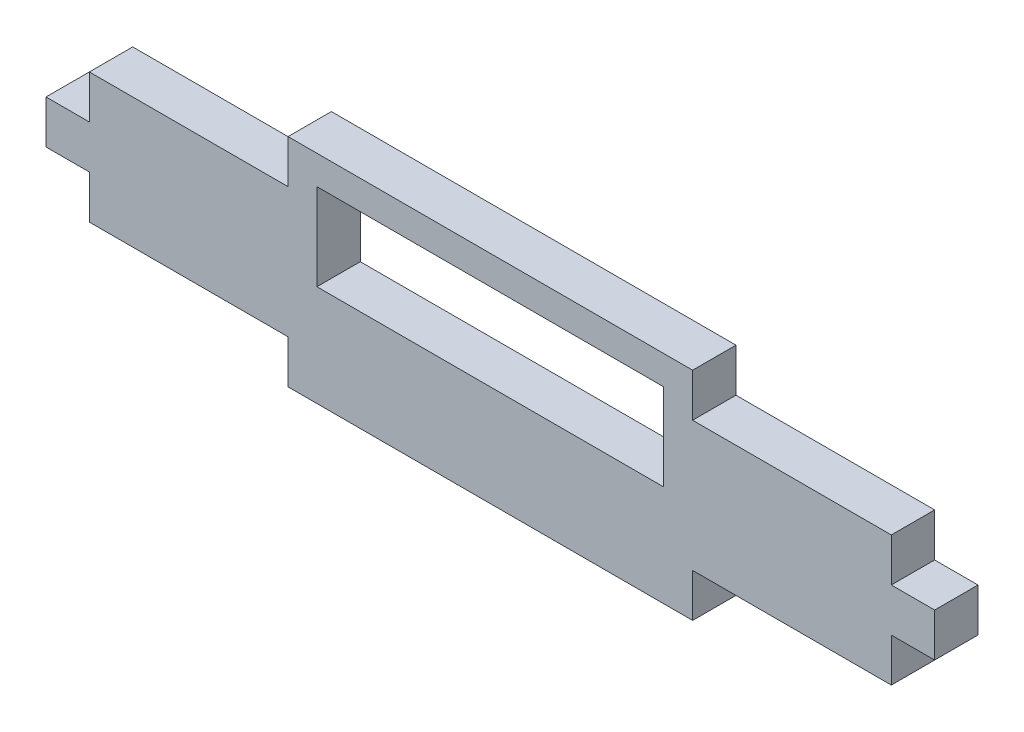
SolidWorks part; units mm, degrees
ref_plane "Front Plane" through (0, 0, 0) normal (0, 0, 1) x (1, 0, 0)
ref_plane "Top Plane" through (0, 0, 0) normal (0, 1, 0) x (1, 0, 0)
ref_plane "Right Plane" through (0, 0, 0) normal (1, 0, 0) x (0, 0, -1)
sketch "Sketch1" plane through (0, 0, 0) normal (0, 0, 1) x (1, 0, 0)
  line L1 (-30.75, -7.5) -> (30.75, -7.5) construction
  line L2 (-30.75, -7.5) -> (-30.75, 7.5) construction
  line L3 (-30.75, 7.5) -> (30.75, 7.5) construction
  line L4 (30.75, -7.5) -> (30.75, 7.5) construction
  line L5 (-30.75, -7.5) -> (30.75, 7.5) construction
  line L6 (-30.75, 7.5) -> (30.75, -7.5) construction
  line L11 (-45.5236, -11.1033) -> (45.5236, 11.1033) construction
  line L12 (-46.4777, 5.9587) -> (46.4777, -5.9587) construction
  line L14 (-14, -7.5) -> (14, -7.5)
  line L19 (30.75, -1.5) -> (30.75, 1.5)
  line L24 (14, 7.5) -> (-14, 7.5)
  line L29 (-30.75, 1.5) -> (-30.75, -1.5)
  line L32 (-14, -7.5) -> (-14, -4.5)
  line L33 (-14, -4.5) -> (-30.75, -4.5) construction
  line L34 (-14, 7.5) -> (-14, 4.5)
  line L35 (-14, 4.5) -> (-30.75, 4.5) construction
  line L38 (14, 7.5) -> (14, 4.5)
  line L39 (14, 4.5) -> (30.75, 4.5) construction
  line L42 (30.75, -4.5) -> (14, -4.5) construction
  line L43 (14, -4.5) -> (14, -7.5)
  line L44 (30.75, 1.5) -> (27.75, 1.5)
  line L45 (27.75, 1.5) -> (27.75, 4.5)
  line L46 (30.75, -1.5) -> (27.75, -1.5)
  line L47 (27.75, -1.5) -> (27.75, -4.5)
  line L48 (-30.75, 1.5) -> (-27.75, 1.5)
  line L49 (-27.75, 1.5) -> (-27.75, 4.5)
  line L50 (-30.75, -1.5) -> (-27.75, -1.5)
  line L51 (-27.75, -1.5) -> (-27.75, -4.5)
  line L52 (14, 4.5) -> (27.75, 4.5)
  line L53 (27.75, -4.5) -> (14, -4.5)
  line L54 (-27.75, 4.5) -> (-14, 4.5)
  line L55 (-14, -4.5) -> (-27.75, -4.5)
  line L57 (-12, -0.5) -> (12, -0.5)
  line L58 (-12, -0.5) -> (-12, 5.5)
  line L59 (-12, 5.5) -> (12, 5.5)
  line L60 (12, -0.5) -> (12, 5.5)
  line L61 (-12, -0.5) -> (12, 5.5) construction
  line L62 (-12, 5.5) -> (12, -0.5) construction
  point P0 (0, 0)
  point P6 (0, 0)
  point P35 (0, 0)
  point P40 (-16.4728, -7.5)
  point P41 (10.2349, -4.5)
  point P42 (0, 2.5)
  point P43 (11.8101, 4.5)
  dimension "D1" = 61.5
  dimension "D2" = 15
  dimension "D3" = 3
  dimension "D4" = 24
  dimension "D5" = 6
  dimension "D6" = 2.5
  dimension "D7" = 28
extrude "Boss-Extrude1" add sketch "Sketch1" along normal blind 3
